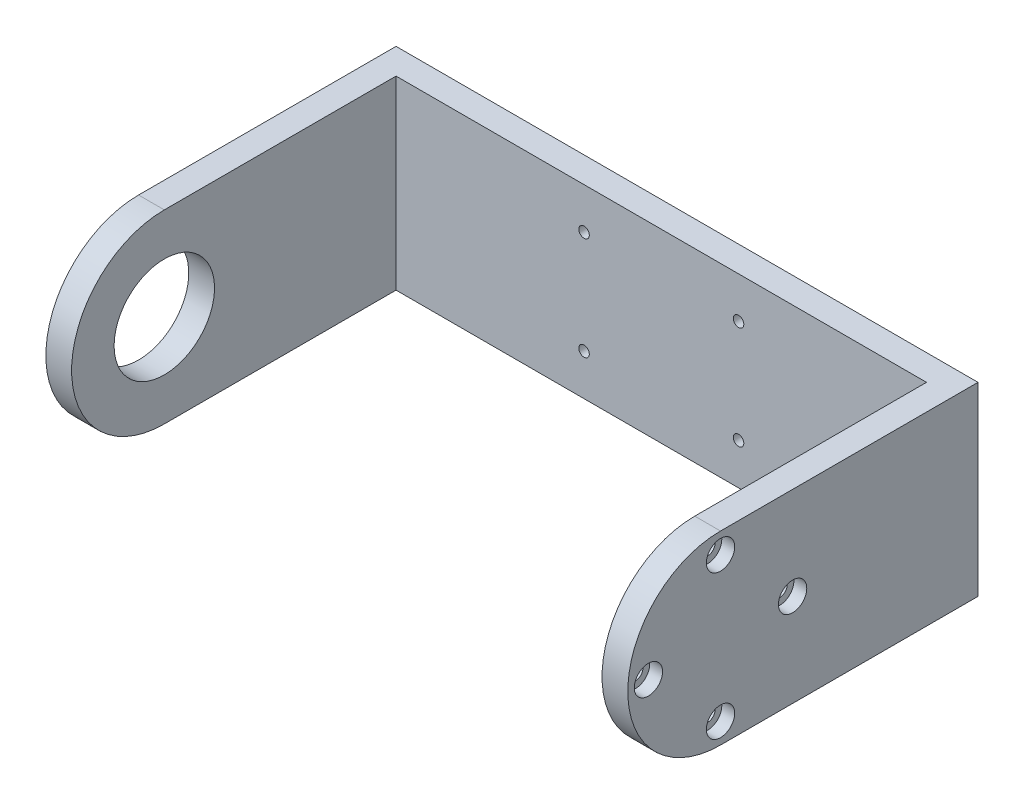
SolidWorks part; units mm, degrees
ref_plane "정면" through (0, 0, 0) normal (0, 0, 1) x (1, 0, 0)
ref_plane "윗면" through (0, 0, 0) normal (0, 1, 0) x (1, 0, 0)
ref_plane "우측면" through (0, 0, 0) normal (1, 0, 0) x (0, 0, -1)
sketch "Sketch1" plane through (0, 0, 0) normal (1, 0, 0) x (0, 0, -1)
  line L0 (0, 18) -> (45, 18)
  line L1 (45, 18) -> (45, -18)
  line L2 (45, -18) -> (0, -18)
  arc A0 (0, 18) -> (0, -18) centre (0, 0) ccw
  circle A1 centre (0, 0) radius 14 construction
  point P7 (0, 14)
  point P8 (14, 0)
  point P9 (0, -14)
  point P10 (-14, 0)
  dimension "D1" = 36
  dimension "D3" = 28
  dimension "D2" = 45
extrude "Boss-Extrude1" add sketch "Sketch1" along normal blind 5 contours L0 L1 L2 A0
sketch "Sketch4" plane through (5, 0, 0) normal (1, 0, 0) x (0, 0, -1)
  circle A0 centre (0, 0) radius 14 construction
  point P3 (0, 14)
  point P4 (0, -14)
  point P5 (14, 0)
  point P6 (-14, 0)
  dimension "D1" = 28
hole_wizard "CBORE for M2.5 Socket Head Cap Screw1" positions "3DSketch3" profile "Sketch5" counterbore size "M2.5" standard "KS" end condition through all
sketch3d "3DSketch3"
  point P0 (5, 14, 0)
  point P3 (5, 0, -14)
  point P6 (5, -14, 0)
  point P9 (5, 0, 14)
sketch "Sketch5" plane through (5, 14, 0) normal (0, 1, 0) x (0, 0, -1)
  line L0 (0, 0) -> (0, 100)
  line L1 (0, 100) -> (1.45, 100)
  line L3 (1.45, 100) -> (1.45, 2.5)
  line L4 (1.45, 2.5) -> (2.75, 2.5)
  line L5 (2.75, 2.5) -> (2.75, 0)
  line L7 (2.75, 0) -> (0, 0)
  line L11 (0, -6.35) -> (0, 107.95) construction
  dimension "Thru Hole Dia." = 2.9
  dimension "Thru Hole Depth" = 100
  dimension "C'Bore Dia." = 5.5
  dimension "C'Bore Depth" = 2.5
sketch "Sketch6" plane through (0, 0, -45) normal (0, 0, -1) x (-1, 0, 0)
  line L1 (-5, -18) -> (108, -18)
  line L2 (-5, -18) -> (-5, 18)
  line L3 (-5, 18) -> (108, 18)
  line L4 (108, -18) -> (108, 18)
  dimension "D1" = 113
  dimension "D2" = 36
extrude "Boss-Extrude2" add sketch "Sketch6" along normal blind 5
ref_plane "Plane1" through (-51.5, 0, 0) normal (1, 0, 0) x (0, 0, -1)
sketch "Sketch7" plane through (-108, 0, 0) normal (-1, 0, 0) x (0, 0, 1)
  line L0 (-50, -18) -> (0, -18)
  line L1 (-50, -18) -> (-50, 18)
  line L2 (-50, 18) -> (0, 18)
  arc A0 (0, -18) -> (0, 18) centre (0, 0) ccw
extrude "Boss-Extrude3" add sketch "Sketch7" against normal blind 5
sketch "Sketch8" plane through (-108, 0, 0) normal (-1, 0, 0) x (0, 0, 1)
  circle A0 centre (0, 0) radius 9.75
extrude "Cut-Extrude1" cut sketch "Sketch8" against normal blind 5 contours A0
sketch "Sketch10" plane through (0, 0, -50) normal (0, 0, -1) x (-1, 0, 0)
  line L0 (51.5, 18) -> (51.5, -18) construction
  line L1 (108, 18) -> (-5, 18) construction
  line L2 (-5, -18) -> (108, -18) construction
  line L3 (51.5, 0) -> (80.3486, 0) construction
  point P6 (66.5, 10)
  point P7 (66.5, -10)
  point P11 (0, 0)
  point P12 (36.5, -10)
  point P13 (36.5, 10)
  dimension "D1" = 20
  dimension "D2" = 10
  dimension "D3" = 30
hole_wizard "M2.5 Tapped Hole1" positions "Sketch11" profile "Sketch12" tap size "M2.5" standard "KS" end condition through all
sketch "Sketch11" plane through (0, 0, -50) normal (0, 0, -1) x (-1, 0, 0)
  point P0 (36.5, 10)
  point P3 (66.5, 10)
  point P6 (66.5, -10)
  point P9 (36.5, -10)
sketch "Sketch12" plane through (-36.5, 10, -50) normal (1, 0, 0) x (0, 1, 0)
  line L0 (0, 0) -> (0, 68)
  line L1 (0, 68) -> (1.025, 68)
  line L2 (1.025, 68) -> (1.025, 0)
  line L5 (1.025, 0) -> (0, 0)
  line L11 (0, -6.35) -> (0, 107.95) construction
  dimension "Thru Tap Drill Dia." = 2.05
  dimension "Thru Tap Drill Depth" = 68
cosmetic thread "Hole Thread1" parameters "D2"=2.5
cosmetic thread "Hole Thread2" parameters "D2"=2.5
cosmetic thread "Hole Thread3" parameters "D2"=2.5
cosmetic thread "Hole Thread4" parameters "D2"=2.5
